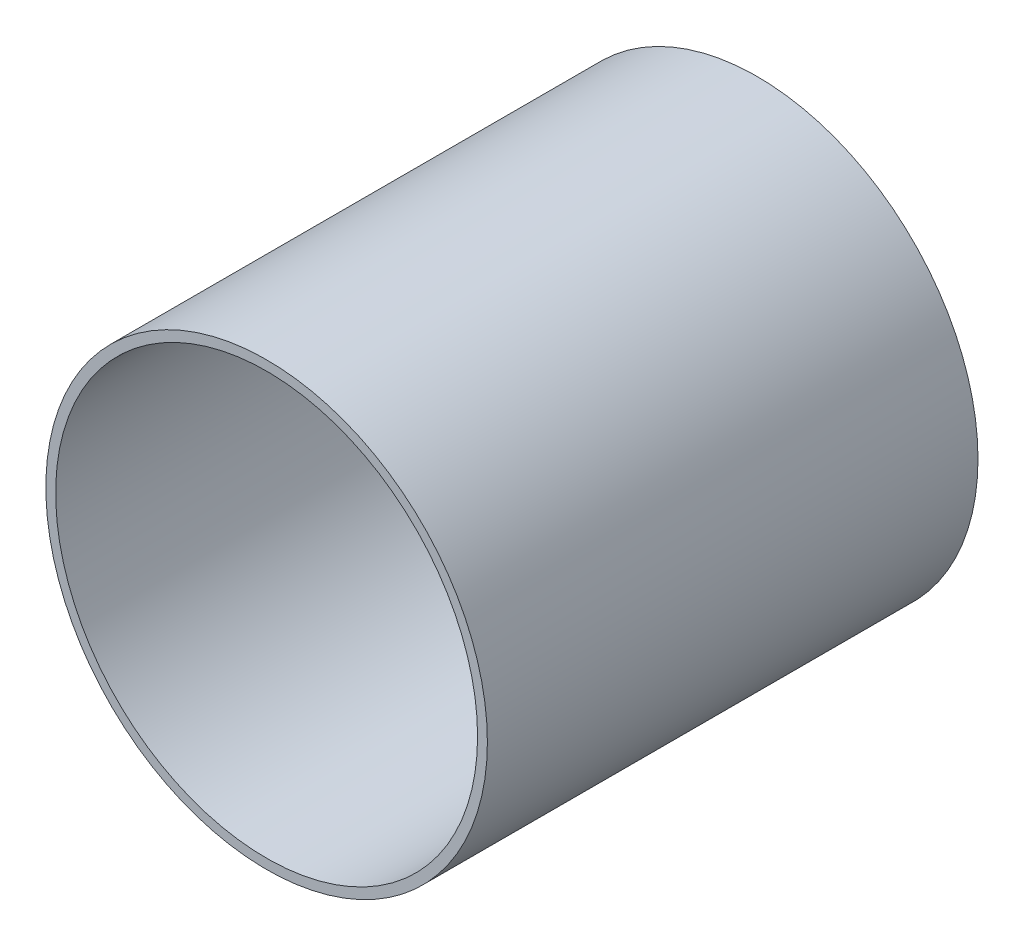
SolidWorks part; units mm, degrees
ref_plane "Front Plane" through (0, 0, 0) normal (0, 0, 1) x (1, 0, 0)
ref_plane "Top Plane" through (0, 0, 0) normal (0, 1, 0) x (1, 0, 0)
ref_plane "Right Plane" through (0, 0, 0) normal (1, 0, 0) x (0, 0, -1)
sketch "Sketch1" plane through (0, 0, 0) normal (0, 0, 1) x (1, 0, 0)
  circle A0 centre (0, 0) radius 45
  circle A1 centre (0, 0) radius 43
extrude "Boss-Extrude1" add sketch "Sketch1" along normal blind 100
